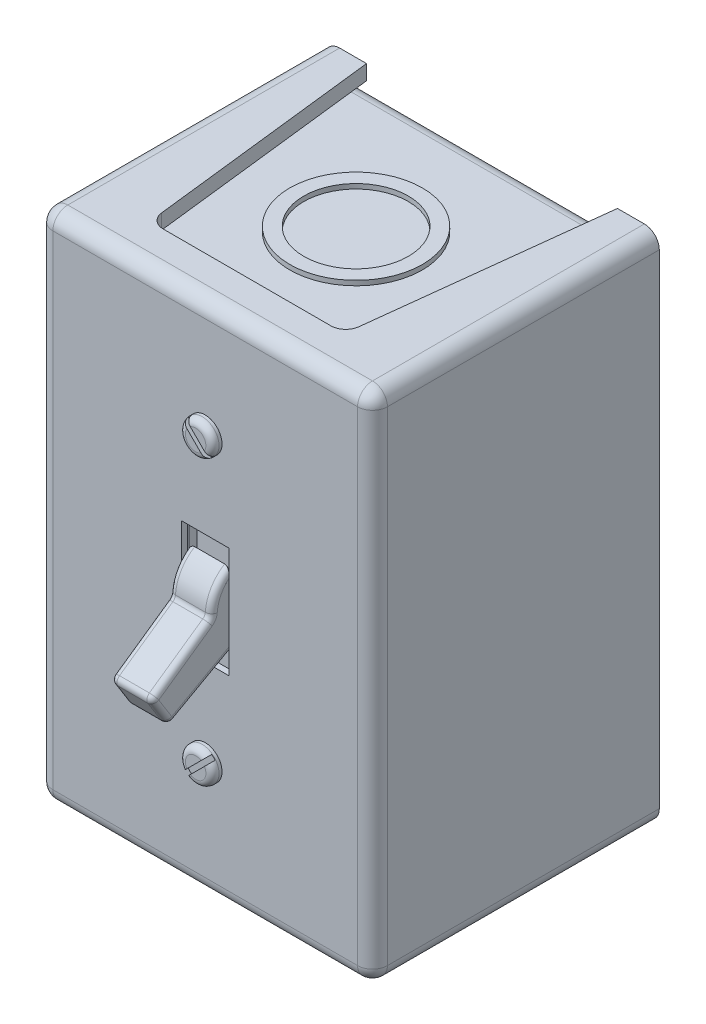
SolidWorks part; units mm, degrees
ref_plane "Front Plane" through (0, 0, 0) normal (0, 0, 1) x (1, 0, 0)
ref_plane "Top Plane" through (0, 0, 0) normal (0, 1, 0) x (1, 0, 0)
ref_plane "Right Plane" through (0, 0, 0) normal (1, 0, 0) x (0, 0, -1)
sketch "Sketch1" plane through (0, 0, 0) normal (0, 0, 1) x (1, 0, 0)
  line L0 (-35.56, -54.61) -> (35.56, 54.61) construction
  line L1 (-35.56, 54.61) -> (35.56, 54.61)
  line L2 (-35.56, 54.61) -> (-35.56, -54.61)
  line L3 (-35.56, -54.61) -> (35.56, -54.61)
  line L4 (35.56, 54.61) -> (35.56, -54.61)
  dimension "D1" = 71.12
  dimension "D2" = 109.22
extrude "Boss-Extrude1" add sketch "Sketch1" along normal blind 60.96
fillet "Fillet1" radius 3.175 8 edges at (0, 54.61, 60.96) (35.56, 0, 60.96) (0, -54.61, 60.96) (-35.56, 0, 60.96) (-35.56, -54.61, 30.48) (35.56, -54.61, 30.48) (-35.56, 54.61, 30.48) (35.56, 54.61, 30.48)
sketch "Sketch2" plane through (0, 54.61, 0) normal (0, 1, 0) x (1, 0, 0)
  line L0 (-20.963, -49.2604) -> (-26.67, 0)
  line L1 (-26.67, 0) -> (26.67, 0)
  line L2 (26.67, 0) -> (20.963, -49.2604)
  line L3 (32.385, 0) -> (-32.385, 0) construction
  line L4 (-35.56, -57.785) -> (-35.56, 0) construction
  line L5 (35.56, 0) -> (35.56, -57.785) construction
  line L6 (35.56, -28.8925) -> (0, -28.8925) construction
  line L7 (-17.8091, -52.07) -> (17.8091, -52.07)
  line L9 (0, -60.96) -> (0, -52.07) construction
  line L11 (32.385, -60.96) -> (-32.385, -60.96) construction
  arc A0 (20.963, -49.2604) -> (17.8091, -52.07) centre (17.8091, -48.895) cw
  circle A1 centre (0, -28.8925) radius 11.1125 construction
  circle A2 centre (0, -28.8925) radius 14.097 construction
  arc A3 (-20.963, -49.2604) -> (-17.8091, -52.07) centre (-17.8091, -48.895) ccw
  point P21 (20.6375, -52.07)
  point P24 (-20.6375, -52.07)
  dimension "D3" = 41.275
  dimension "D4" = 22.225
  dimension "D5" = 28.194
  dimension "D7" = 3.175
  dimension "D1" = 8.89
  dimension "D2" = 8.89
  dimension "D6" = 8.89
extrude "Cut-Extrude1" cut sketch "Sketch2" against normal blind 3.175
sketch "Sketch3" plane through (0, 51.435, 0) normal (0, 1, 0) x (1, 0, 0)
  circle A0 centre (0, -28.8925) radius 11.1125 construction
  circle A1 centre (0, -28.8925) radius 14.097 construction
  circle A2 centre (0, -28.8925) radius 11.1125
  circle A3 centre (0, -28.8925) radius 14.097
extrude "Boss-Extrude5" add sketch "Sketch3" along normal blind 1.016
mirror "Mirror1" about plane through (0, 0, 0) normal (0, 1, 0) of "Boss-Extrude5", "Cut-Extrude1"
sketch "Sketch5" plane through (0, 0, 0) normal (0, 0, -1) x (-1, 0, 0)
  line L12 (-32.385, -51.435) -> (-29.845, -51.435)
  line L13 (32.385, -51.435) -> (32.385, 51.435)
  line L14 (32.385, 51.435) -> (29.845, 51.435)
  line L15 (-32.385, 51.435) -> (-32.385, -51.435)
  line L16 (-32.385, -51.435) -> (32.385, -51.435)
  line L17 (32.385, -51.435) -> (32.385, 51.435)
  line L19 (-32.385, 51.435) -> (-32.385, -51.435)
  line L28 (-29.845, -51.435) -> (-29.845, -48.26)
  line L30 (-29.845, -48.26) -> (29.845, -48.26)
  line L32 (29.845, -48.26) -> (29.845, -51.435)
  line L34 (29.845, -51.435) -> (32.385, -51.435)
  line L36 (29.845, 51.435) -> (29.845, 48.26)
  line L38 (29.845, 48.26) -> (-29.845, 48.26)
  line L40 (-29.845, 48.26) -> (-29.845, 51.435)
  line L42 (-29.845, 51.435) -> (-32.385, 51.435)
  line L43 (32.385, 51.435) -> (-32.385, 51.435)
  dimension "D1" = 3.175
extrude "Cut-Extrude-Thin1" cut sketch "Sketch5" against normal blind 53.975 thin thin type one direction reverse wall 0.508
sketch "Sketch4" plane through (0, 0, 0) normal (0, 0, -1) x (-1, 0, 0)
  line L0 (-20.32, -38.1) -> (20.32, 38.1) construction
  line L1 (-20.32, 38.1) -> (20.32, 38.1) construction
  line L2 (-20.32, 38.1) -> (-20.32, -38.1) construction
  line L3 (-20.32, -38.1) -> (20.32, -38.1) construction
  line L4 (20.32, 38.1) -> (20.32, -38.1) construction
  line L5 (0, 28.9687) -> (0, -28.9687) construction
  circle A0 centre (-20.32, 38.1) radius 3.175
  circle A1 centre (20.32, 38.1) radius 3.175
  circle A3 centre (20.32, -38.1) radius 3.175
  circle A4 centre (0, 28.9687) radius 11.1125
  dimension "D3" = 6.35
  dimension "D4" = 6.35
  dimension "D5" = 22.225
  dimension "D6" = 57.9374
  dimension "D1" = 76.2
  dimension "D2" = 40.64
extrude "Cut-Extrude3" cut sketch "Sketch4" against normal blind 1.016
fillet "Fillet6" radius 3.175 2 edges at (0, 50.927, 0) (0, -50.927, 0)
sketch "Sketch9" plane through (0, 0, 60.96) normal (0, 0, 1) x (1, 0, 0)
  line L0 (-5.08, -11.7475) -> (5.08, 11.7475) construction
  line L1 (-5.08, 11.7475) -> (5.08, 11.7475)
  line L2 (-5.08, 11.7475) -> (-5.08, -11.7475)
  line L4 (-5.08, -11.7475) -> (5.08, -11.7475)
  line L5 (5.08, 11.7475) -> (5.08, -11.7475)
  dimension "D1" = 10.16
  dimension "D2" = 23.495
extrude "Cut-Extrude6" cut sketch "Sketch9" against normal blind 1.27
sketch "Sketch10" plane through (0, 0, 59.69) normal (0, 0, 1) x (1, 0, 0)
  line L0 (-4.7625, -15.0812) -> (4.7625, 15.0812) construction
  line L1 (-4.7625, 15.0812) -> (4.7625, 15.0812)
  line L2 (-4.7625, 15.0812) -> (-4.7625, -15.0812)
  line L3 (-4.7625, -15.0812) -> (4.7625, -15.0813)
  line L4 (4.7625, 15.0812) -> (4.7625, -15.0813)
  dimension "D1" = 9.525
  dimension "D2" = 30.1625
extrude "Cut-Extrude7" cut sketch "Sketch10" against normal blind 1.778
sketch "Sketch11" plane through (0, 0, 0) normal (1, 0, 0) x (0, 0, -1)
  line L0 (-78.486, 3.81) -> (-78.486, -3.81)
  line L1 (-78.486, -3.81) -> (-62.8111, -4.6315)
  line L2 (-78.486, 3.81) -> (-62.8111, 4.6315)
  line L3 (-55.372, 8.763) -> (-55.372, -8.763)
  line L4 (-64.135, 38.8884) -> (-64.135, -38.8884) construction
  line L5 (-60.96, -51.435) -> (-60.96, 51.435) construction
  line L6 (-64.135, 0) -> (-78.486, 0) construction
  arc A0 (-55.372, 8.763) -> (-62.8111, 4.6315) centre (-55.372, 0) ccw
  arc A1 (-62.8111, -4.6315) -> (-55.372, -8.763) centre (-55.372, 0) ccw
  dimension "D1" = 3.175
  dimension "D2" = 7.62
  dimension "D3" = 3
  dimension "D4" = 17.526
  dimension "D5" = 17.526
extrude "Boss-Extrude3" add sketch "Sketch11" along normal mid plane 8.89 separate body
fillet "Fillet5" radius 1.27 17 edges at (4.445, 7.6608, 59.6267) (4.445, 0, 55.372) (4.445, -4.2207, 70.6485) (0, -4.6315, 62.8111) (4.445, -7.6608, 59.6267) (0, -8.763, 55.372) (-4.445, -4.2207, 70.6485) (-4.445, -7.6608, 59.6267) (-4.445, 0, 55.372) (-4.445, 7.6608, 59.6267) (0, 4.6315, 62.8111) (4.445, 4.2207, 70.6485) (-4.445, 4.2207, 70.6485) (0, 3.81, 78.486) (4.445, 0, 78.486) (0, -3.81, 78.486) (-4.445, 0, 78.486)
move or copy body "Body-Move/Copy1" bodies to move or copy 112 copy no rotation origin (0, 0, 55.372) rotation axis (1, 0, 0) rotation angle 32
sketch "Sketch15" plane through (0, 0, 60.96) normal (0, 0, 1) x (1, 0, 0)
  line L0 (0, 30.1625) -> (0, -30.1625) construction
  circle A0 centre (0, 30.1625) radius 3.575
  circle A1 centre (0, -30.1625) radius 3.575
  dimension "D2" = 7.1501
  dimension "D1" = 60.325
extrude "Boss-Extrude6" add sketch "Sketch15" along normal blind 2.032
fillet "Fillet7" radius 1.397 2 edges at (3.5751, -30.1625, 62.992) (3.5751, 30.1625, 62.992)
sketch "Sketch16" plane through (0, 0, 62.992) normal (0, 0, 1) x (1, 0, 0)
  line L0 (-5.178, 35.3405) -> (5.178, 24.9845)
  line L1 (0, 30.1625) -> (-6.7041, 30.1625) construction
  circle A0 centre (0, 30.1625) radius 3.575 construction
  circle A1 centre (0, 30.1625) radius 3.575 construction
  circle A2 centre (0, -30.1625) radius 3.575 construction
  circle A3 centre (0, -30.1625) radius 3.575 construction
  dimension "D1" = 45
extrude "Cut-Extrude-Thin2" cut sketch "Sketch16" against normal blind 1.27 thin thin type mid plane wall 1.016
mirror "Mirror3" about plane through (0, 0, 0) normal (0, 1, 0) of "Cut-Extrude-Thin2"
ref_plane "Plane1" [suppressed] through (15.875, 0, 0) normal (1, 0, 0) x (0, 0, -1)
sketch "Sketch17" [suppressed] plane through (15.875, 0, 0) normal (1, 0, 0) x (0, 0, -1)
  line L0 (-60.96, -22.86) -> (-72.0725, -22.86) construction
  line L1 (-60.96, -51.435) -> (-60.96, 51.435) construction
  line L2 (0, -54.61) -> (-57.785, -54.61) construction
  line L3 (-60.96, -30.7975) -> (-64.135, -30.7975)
  line L4 (-60.96, -30.7975) -> (-60.96, -22.86)
  line L5 (-60.96, -22.86) -> (-72.0725, -22.86)
  arc A0 (-64.135, -30.7975) -> (-72.0725, -22.86) centre (-64.135, -22.86) cw
  dimension "D1" = 31.75
  dimension "D2" = 15.875
  dimension "D3" = 11.1125
revolve "Revolve1" [suppressed] add sketch "Sketch17" angle 360 about L0
